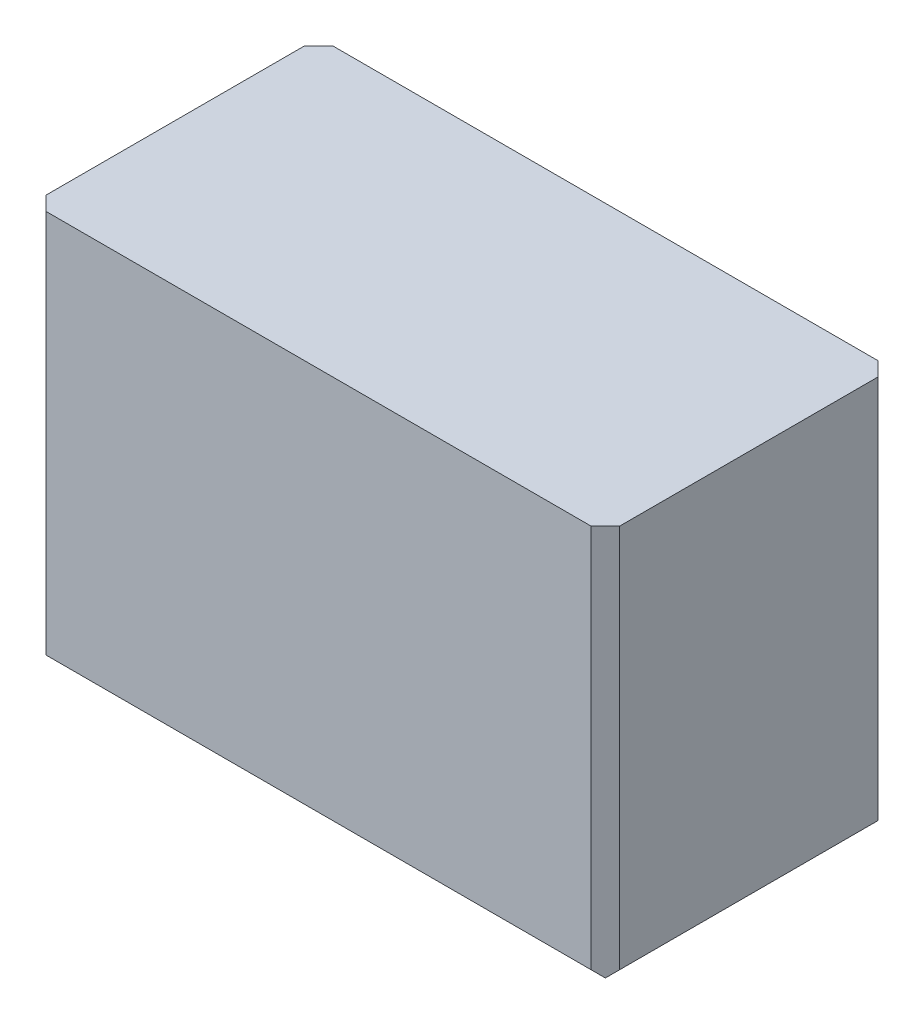
SolidWorks part; units mm, degrees
ref_plane "前视基准面" through (0, 0, 0) normal (0, 0, 1) x (1, 0, 0)
ref_plane "上视基准面" through (0, 0, 0) normal (0, 1, 0) x (1, 0, 0)
ref_plane "右视基准面" through (0, 0, 0) normal (1, 0, 0) x (0, 0, -1)
sketch "草图1" plane through (0, 0, 0) normal (0, 0, 1) x (1, 0, 0)
  line L1 (-20, 13.9) -> (20, 13.9)
  line L2 (-20, 13.9) -> (-20, -13.9)
  line L3 (-20, -13.9) -> (20, -13.9)
  line L4 (20, 13.9) -> (20, -13.9)
  line L5 (-20, 13.9) -> (20, -13.9) construction
  line L6 (-20, -13.9) -> (20, 13.9) construction
  point P0 (0, 0)
  dimension "D1" = 40
  dimension "D2" = 27.8
extrude "凸台-拉伸1" add sketch "草图1" along normal blind 20
chamfer "倒角1" distance 1 angle 45 2 edges at (-20, -13.9, 10) (20, -13.9, 10)
chamfer "倒角2" distance 1 angle 45 2 edges at (0, -13.9, 0) (0, -13.9, 20)
chamfer "倒角3" distance 1 angle 45 4 edges at (20, 0.5, 0) (20, 0.5, 20) (-20, 0.5, 20) (-20, 0.5, 0)
